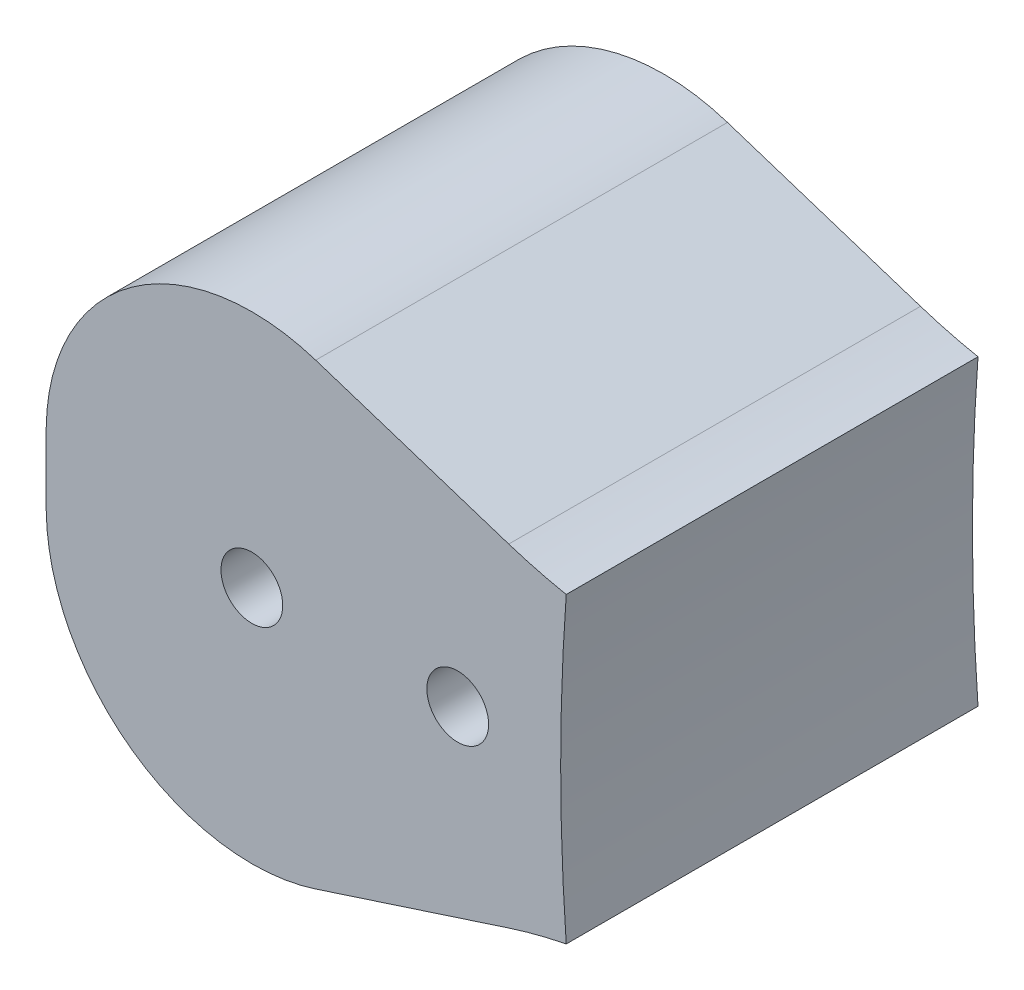
SolidWorks part; units mm, degrees
ref_plane "前视基准面" through (0, 0, 0) normal (0, 0, 1) x (1, 0, 0)
ref_plane "上视基准面" through (0, 0, 0) normal (0, 1, 0) x (1, 0, 0)
ref_plane "右视基准面" through (0, 0, 0) normal (1, 0, 0) x (0, 0, -1)
sketch "草图1" plane through (0, 0, 0) normal (0, 0, 1) x (1, 0, 0)
  line L2 (-102.5221, 8.0763) -> (-111.8985, 11.1229)
  line L3 (-111.8985, -11.1229) -> (-102.5221, -8.0763)
  line L4 (-102.5221, 8.0763) -> (-111.8985, 11.1229)
  line L5 (-111.8985, -11.1229) -> (-102.5221, -8.0763)
  arc A0 (-106.4266, -0.4635) -> (-103.5734, 0.4635) centre (-105, 0) ccw construction
  arc A1 (-103.5734, 0.4635) -> (-106.4266, -0.4635) centre (-105, 0) ccw construction
  arc A2 (-116.4266, -0.4635) -> (-113.5734, 0.4635) centre (-115, 0) ccw construction
  arc A3 (-113.5734, 0.4635) -> (-116.4266, -0.4635) centre (-115, 0) ccw construction
  arc A4 (-106.4266, -0.4635) -> (-103.5734, 0.4635) centre (-105, 0) ccw
  arc A5 (-103.5734, 0.4635) -> (-106.4266, -0.4635) centre (-105, 0) ccw
  arc A6 (-99.7294, -7.3513) -> (-102.5221, -8.0763) centre (-95.1057, -30.9017) ccw
  arc A7 (-99.7294, 7.3513) -> (-99.7294, -7.3513) centre (0, 0) ccw
  arc A8 (-102.5221, 8.0763) -> (-99.7294, 7.3513) centre (-95.1057, 30.9017) ccw
  arc A9 (-111.8985, 11.1229) -> (-124.9877, 1.7526) centre (-114.9887, 1.6124) ccw
  arc A10 (-124.9877, 1.7526) -> (-124.9877, -1.7526) centre (0, 0) ccw
  arc A11 (-124.9877, -1.7526) -> (-111.8985, -11.1229) centre (-114.9887, -1.6124) ccw
  arc A12 (-99.7294, -7.3513) -> (-102.5221, -8.0763) centre (-95.1057, -30.9017) ccw
  arc A13 (-99.7294, 7.3513) -> (-99.7294, -7.3513) centre (0, 0) ccw
  arc A14 (-102.5221, 8.0763) -> (-99.7294, 7.3513) centre (-95.1057, 30.9017) ccw
  arc A15 (-111.8985, 11.1229) -> (-124.9877, 1.7526) centre (-114.9887, 1.6124) ccw
  arc A16 (-124.9877, 1.7526) -> (-124.9877, -1.7526) centre (0, 0) ccw
  arc A17 (-124.9877, -1.7526) -> (-111.8985, -11.1229) centre (-114.9887, -1.6124) ccw
  arc A18 (-116.4266, -0.4635) -> (-113.5734, 0.4635) centre (-115, 0) ccw
  arc A19 (-113.5734, 0.4635) -> (-116.4266, -0.4635) centre (-115, 0) ccw
  dimension "D1" = 0
extrude "凸台-拉伸1" add sketch "草图1" along normal blind 20
